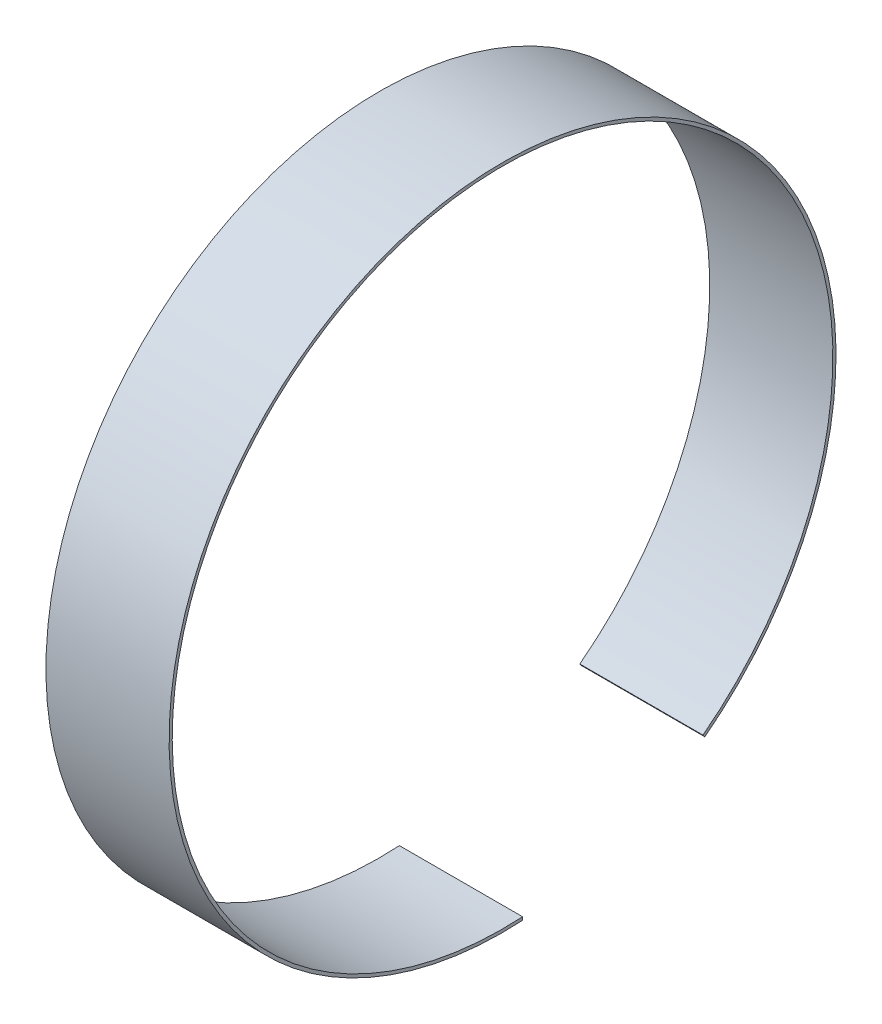
SolidWorks part; units mm, degrees
material "6061 Alloy"
ref_plane "Front Plane" through (0, 0, 0) normal (0, 0, 1) x (1, 0, 0)
ref_plane "Top Plane" through (0, 0, 0) normal (0, 1, 0) x (1, 0, 0)
ref_plane "Right Plane" through (0, 0, 0) normal (1, 0, 0) x (0, 0, -1)
sketch "Sketch1" plane through (0, 0, 0) normal (1, 0, 0) x (0, 0, -1)
  line L0 (4.5, -55.7107) -> (4.5, -85.7107)
  line L1 (4.5, -55.7107) -> (45.5, -55.7107)
  line L2 (4.5, -85.7107) -> (45.5, -85.7107)
  line L3 (45.5, -55.7107) -> (45.5, -85.7107)
  line L4 (4.5, -55.7107) -> (45.5, -85.7107) construction
  line L5 (4.5, -85.7107) -> (45.5, -55.7107) construction
  line L6 (4.5, -74.8649) -> (4.458, -74.1661)
  line L7 (45.5, -59.6217) -> (45.0753, -59.0653)
  circle A0 centre (0, 0) radius 75
  circle A1 centre (0, 0) radius 74.3
  point P5 (25, -70.7107)
  dimension "D1" = 150
  dimension "D2" = 0.7
  dimension "D3" = 41
  dimension "D4" = 30
  dimension "D5" = 25
extrude "Boss-Extrude1" add sketch "Sketch1" along normal mid plane 27.7 contours A1 L3 A0 L6 | A1 L6 L0 | A1 L7 L3
